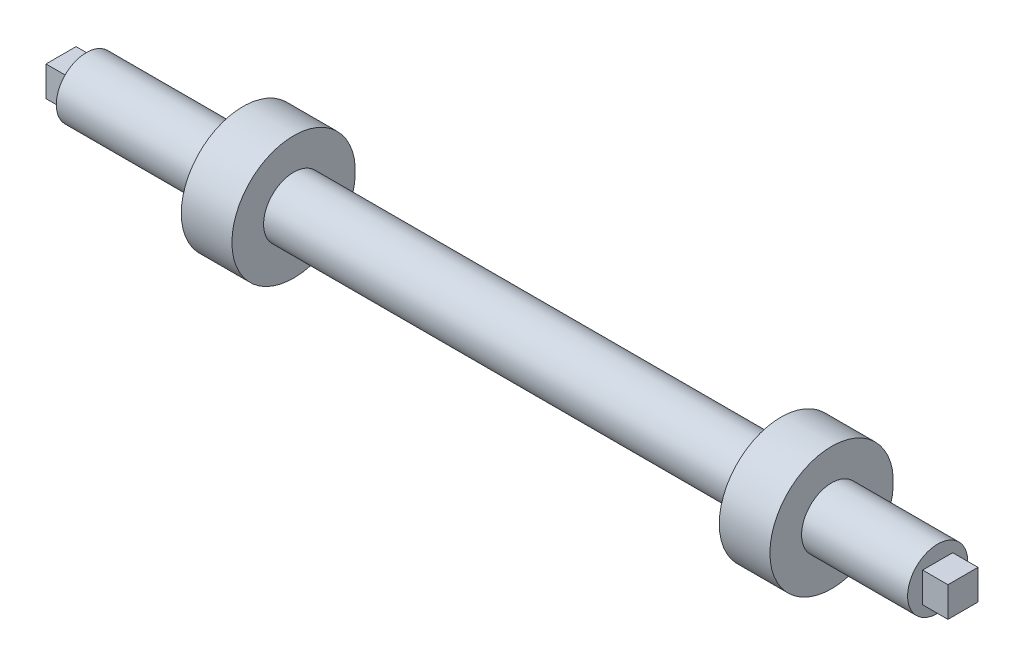
SolidWorks part; units mm, degrees
ref_plane "Plan de face" through (0, 0, 0) normal (0, 0, 1) x (1, 0, 0)
ref_plane "Plan de dessus" through (0, 0, 0) normal (0, 1, 0) x (1, 0, 0)
ref_plane "Plan de droite" through (0, 0, 0) normal (1, 0, 0) x (0, 0, -1)
sketch "Esquisse1" plane through (0, 0, 0) normal (0, 1, 0) x (1, 0, 0)
  line L0 (0, 0) -> (0, 4.75)
  line L1 (0, 4.75) -> (134.5, 4.75)
  line L2 (134.5, 4.75) -> (134.5, 0)
  line L24 (24.75, 0) -> (24.75, -5)
  line L25 (24.75, -5) -> (32.75, -5)
  line L26 (32.75, -5) -> (32.75, 0)
  line L27 (109.75, 0) -> (109.75, -5)
  line L28 (109.75, -5) -> (117.75, -5)
  line L29 (117.75, -5) -> (117.75, 0)
  line L30 (0, 0) -> (24.75, 0)
  line L31 (32.75, 0) -> (109.75, 0)
  line L32 (117.75, 0) -> (134.5, 0)
  dimension "D2" = 24.75
  dimension "D3" = 8
  dimension "D4" = 8
  dimension "D5" = 16.75
  dimension "D6" = 5
  dimension "D7" = 5
  dimension "D8" = 4.75
  dimension "D9" = 5
  dimension "D10" = 5
  dimension "D11" = 93
revolve "Révolution1" add sketch "Esquisse1" angle 360 about L1
sketch "Esquisse5" plane through (134.5, 0, 0) normal (1, 0, 0) x (0, 0, -1)
  line L0 (2.375, 2.375) -> (2.375, -2.375)
  line L9 (2.375, 2.375) -> (7.125, 2.375)
  line L10 (7.125, 2.375) -> (7.125, -2.375)
  line L11 (7.125, -2.375) -> (2.375, -2.375)
extrude "Boss.-Extru.3" add sketch "Esquisse5" along normal blind 4
sketch "Esquisse6" plane through (0, 0, 0) normal (-1, 0, 0) x (0, 0, 1)
  line L8 (-4.75, 2.375) -> (-7.125, 2.375)
  line L9 (-7.125, 2.375) -> (-7.125, -2.375)
  line L10 (-7.125, -2.375) -> (-2.375, -2.375)
  line L11 (-2.375, -2.375) -> (-2.375, 2.375)
  line L12 (-2.375, 2.375) -> (-4.75, 2.375)
extrude "Boss.-Extru.4" add sketch "Esquisse6" along normal blind 4
